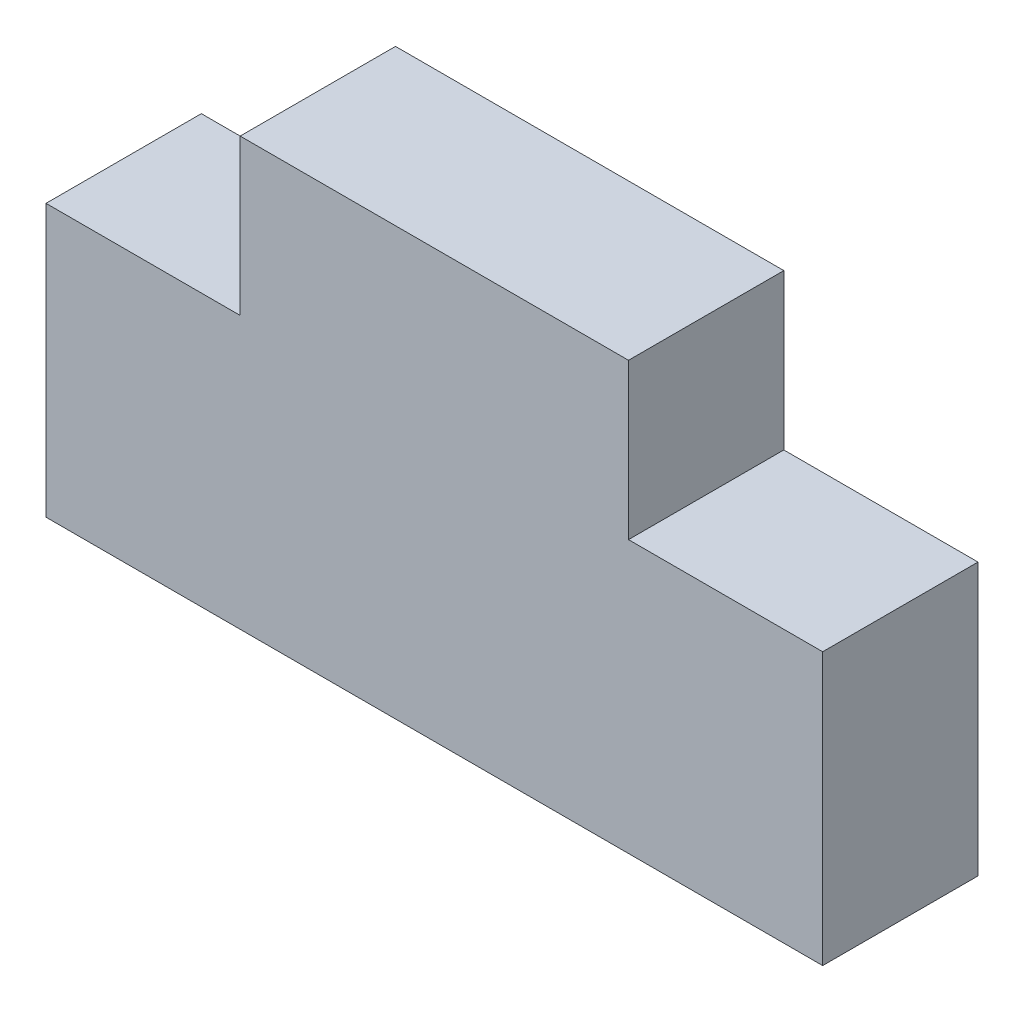
SolidWorks part; units mm, degrees
ref_plane "Front Plane" through (0, 0, 0) normal (0, 0, 1) x (1, 0, 0)
ref_plane "Top Plane" through (0, 0, 0) normal (0, 1, 0) x (1, 0, 0)
ref_plane "Right Plane" through (0, 0, 0) normal (1, 0, 0) x (0, 0, -1)
sketch "Sketch1" plane through (0, 0, 0) normal (0, 0, 1) x (1, 0, 0)
  line L0 (0, 0) -> (0, 5.1375) construction
  line L1 (0, 0) -> (7.9844, 0) construction
  line L2 (-2.5, 5.5) -> (2.5, 5.5)
  line L3 (2.5, 5.5) -> (2.5, 3.5)
  line L4 (2.5, 3.5) -> (5, 3.5)
  line L5 (5, 3.5) -> (5, 0)
  line L6 (5, 0) -> (-5, 0)
  line L7 (-5, 3.5) -> (-5, 0)
  line L8 (-2.5, 3.5) -> (-5, 3.5)
  line L9 (-2.5, 5.5) -> (-2.5, 3.5)
  point P13 (0, 5.5)
  dimension "D1" = 2.5
  dimension "D2" = 5
  dimension "D3" = 2
  dimension "D4" = 5.5
extrude "Boss-Extrude1" add sketch "Sketch1" along normal blind 2
